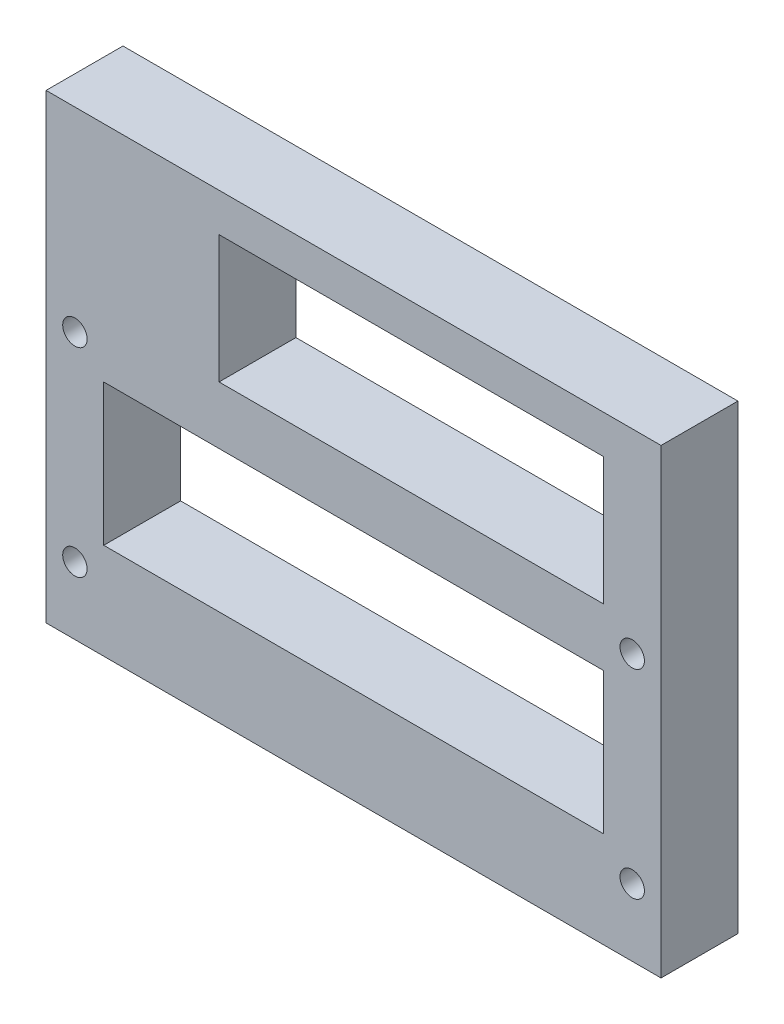
SolidWorks part; units mm, degrees
ref_plane "Front" through (0, 0, 0) normal (0, 0, 1) x (1, 0, 0)
ref_plane "Top" through (0, 0, 0) normal (0, 1, 0) x (1, 0, 0)
ref_plane "Right" through (0, 0, 0) normal (1, 0, 0) x (0, 0, -1)
sketch "Sketch1" plane through (0, 0, 0) normal (0, 0, 1) x (1, 0, 0)
  line L0 (-7.5, 25.9) -> (0, 18.4)
  line L1 (0, 0) -> (65, 0)
  line L2 (0, 0) -> (0, 18.4)
  line L3 (0, 18.4) -> (65, 18.4)
  line L4 (65, 0) -> (65, 18.4)
  line L5 (0, 25.9) -> (72.5, 25.9)
  line L6 (72.5, 25.9) -> (72.5, -7.5)
  line L7 (72.5, -7.5) -> (-7.5, -7.5)
  line L8 (-7.5, -7.5) -> (-7.5, 25.9)
  line L9 (-7.5, 25.9) -> (0, 25.9)
  line L10 (-7.5, -7.5) -> (0, 0)
  line L11 (72.5, -7.5) -> (65, 0)
  line L12 (72.5, 25.9) -> (65, 18.4)
  line L13 (-7.5, 25.9) -> (-7.5, 47.5)
  line L14 (-7.5, 47.5) -> (72.5, 47.5)
  line L15 (72.5, 47.5) -> (72.5, 25.9)
  line L16 (-7.5, -7.5) -> (-7.5, -12.5)
  line L17 (-7.5, -12.5) -> (72.5, -12.5)
  line L18 (72.5, -12.5) -> (72.5, -7.5)
  line L19 (65, 47.5) -> (65, 42.5)
  line L20 (65, 42.5) -> (15, 42.5)
  line L21 (15, 42.5) -> (15, 25.9)
  line L22 (65, 42.5) -> (65, 25.9)
  line L23 (0, 42.5) -> (0, 25.9)
  circle A0 centre (-3.75, 22.15) radius 1.5875
  circle A1 centre (-3.75, -3.75) radius 1.5875
  circle A2 centre (68.75, -3.75) radius 1.5875
  circle A3 centre (68.75, 22.15) radius 1.5875
  dimension "D7" = 21.6
  dimension "D1" = 65
  dimension "D2" = 18.4
  dimension "D3" = 7.5
  dimension "D4" = 72.5
  dimension "D5" = 33.4
  dimension "D6" = 80
  dimension "D8" = 5
  dimension "D9" = 5
  dimension "D10" = 50
extrude "Boss-Extrude1" add sketch "Sketch1" along normal blind 10
